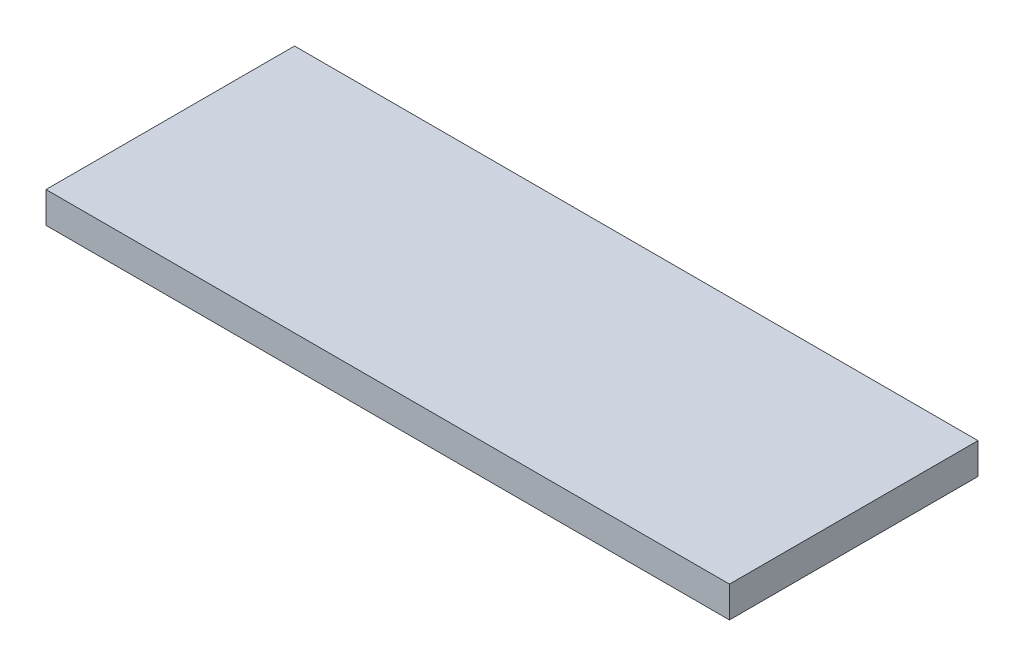
SolidWorks part; units mm, degrees
ref_plane "前视基准面" through (0, 0, 0) normal (0, 0, 1) x (1, 0, 0)
ref_plane "上视基准面" through (0, 0, 0) normal (0, 1, 0) x (1, 0, 0)
ref_plane "右视基准面" through (0, 0, 0) normal (1, 0, 0) x (0, 0, -1)
sketch "草图1" plane through (0, 0, 0) normal (0, 1, 0) x (1, 0, 0)
  line L1 (-22, 8) -> (22, 8)
  line L2 (-22, 8) -> (-22, -8)
  line L3 (-22, -8) -> (22, -8)
  line L4 (22, 8) -> (22, -8)
  line L5 (-22, 8) -> (22, -8) construction
  line L6 (-22, -8) -> (22, 8) construction
  point P0 (0, 0)
  dimension "D1" = 16
  dimension "D2" = 44
extrude "凸台-拉伸1" add sketch "草图1" along normal blind 2
